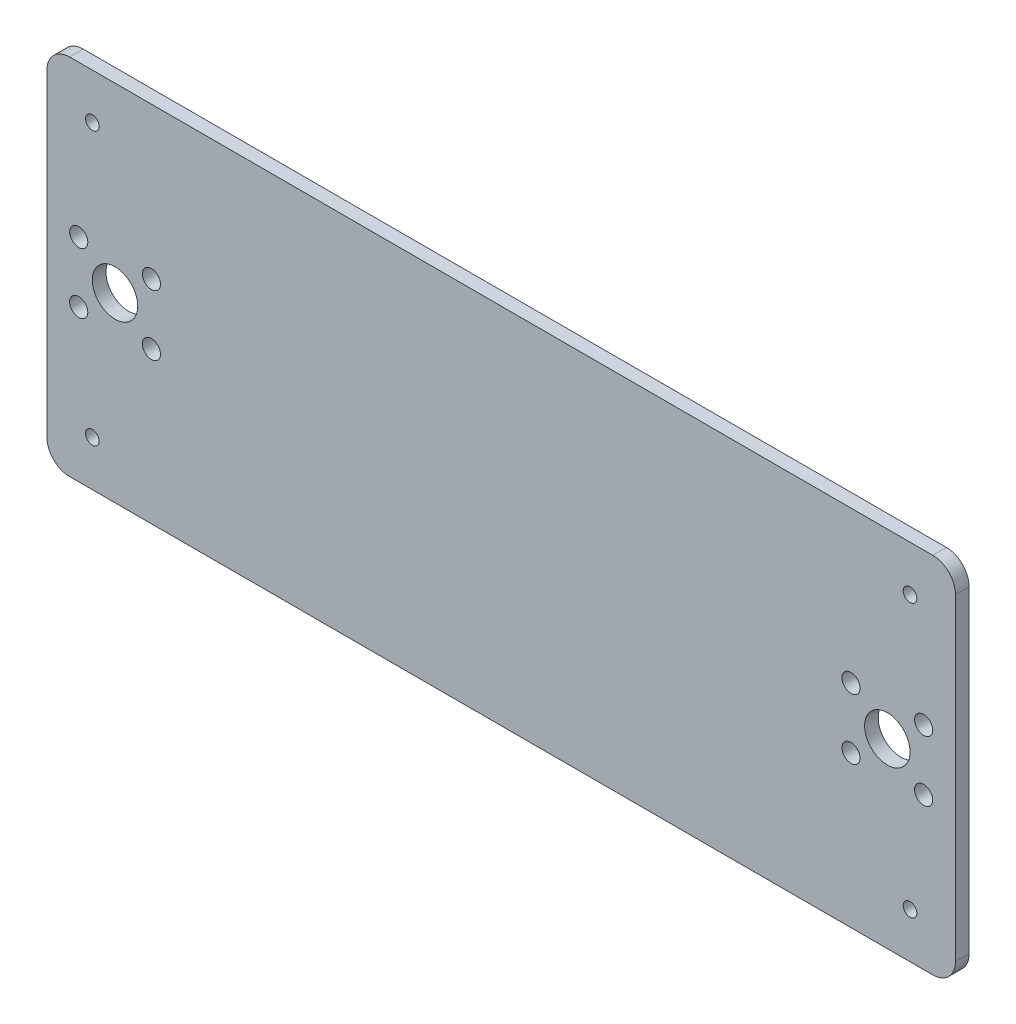
SolidWorks part; units mm, degrees
ref_plane "Plano frontal" through (0, 0, 0) normal (0, 0, 1) x (1, 0, 0)
ref_plane "Plano superior" through (0, 0, 0) normal (0, 1, 0) x (1, 0, 0)
ref_plane "Plano direito" through (0, 0, 0) normal (1, 0, 0) x (0, 0, -1)
sketch "Esboço1" plane through (0, 0, 0) normal (0, 0, 1) x (1, 0, 0)
  line L0 (-118.8193, 0) -> (118.0055, 0) construction
  line L1 (95, -40) -> (-95, -40)
  line L2 (100, -35) -> (100, 35)
  line L3 (95, 40) -> (-95, 40)
  line L4 (-100, -35) -> (-100, 35)
  line L5 (100, -40) -> (-100, 40) construction
  line L6 (100, 40) -> (-100, -40) construction
  line L10 (85, 0) -> (74.4381, -10.5619) construction
  line L12 (85, -15.569) -> (85, 16.1526) construction
  line L13 (0, -60.6919) -> (0, 55.4447) construction
  circle A0 centre (-90, 30) radius 1.5
  circle A1 centre (90, 30) radius 1.5
  circle A2 centre (90, -30) radius 1.5
  circle A3 centre (-90, -30) radius 1.5
  arc A4 (100, 35) -> (95, 40) centre (95, 35) ccw
  arc A5 (95, -40) -> (100, -35) centre (95, -35) ccw
  arc A6 (-95, -40) -> (-100, -35) centre (-95, -35) cw
  arc A7 (-95, 40) -> (-100, 35) centre (-95, 35) ccw
  circle A8 centre (-85, 0) radius 5
  circle A9 centre (85, 0) radius 5
  circle A11 centre (93, 6.67) radius 2
  circle A12 centre (93, -6.67) radius 2
  circle A13 centre (77, -6.67) radius 2
  circle A14 centre (77, 6.67) radius 2
  circle A15 centre (-77, -6.67) radius 2
  circle A16 centre (-93, -6.67) radius 2
  circle A17 centre (-93, 6.67) radius 2
  circle A18 centre (-77, 6.67) radius 2
  point P0 (0, 0)
  dimension "D5" = 3
  dimension "D4" = 10
  dimension "D8" = 10
  dimension "D9" = 10
  dimension "D10" = 90
  dimension "D11" = 5
  dimension "D12" = 15
  dimension "D13" = 10
  dimension "D14" = 10
  dimension "D15" = 15
  dimension "D16" = 4
  dimension "D17" = 7
  dimension "D18" = 4
  dimension "D19" = 7
  dimension "D20" = 6.67
  dimension "D21" = 6.67
  dimension "D1" = 80
  dimension "D2" = 200
  dimension "D3" = 10
  dimension "D6" = 2
  dimension "D7" = 2
extrude "Ressalto-extrusão1" add sketch "Esboço1" along normal blind 3
